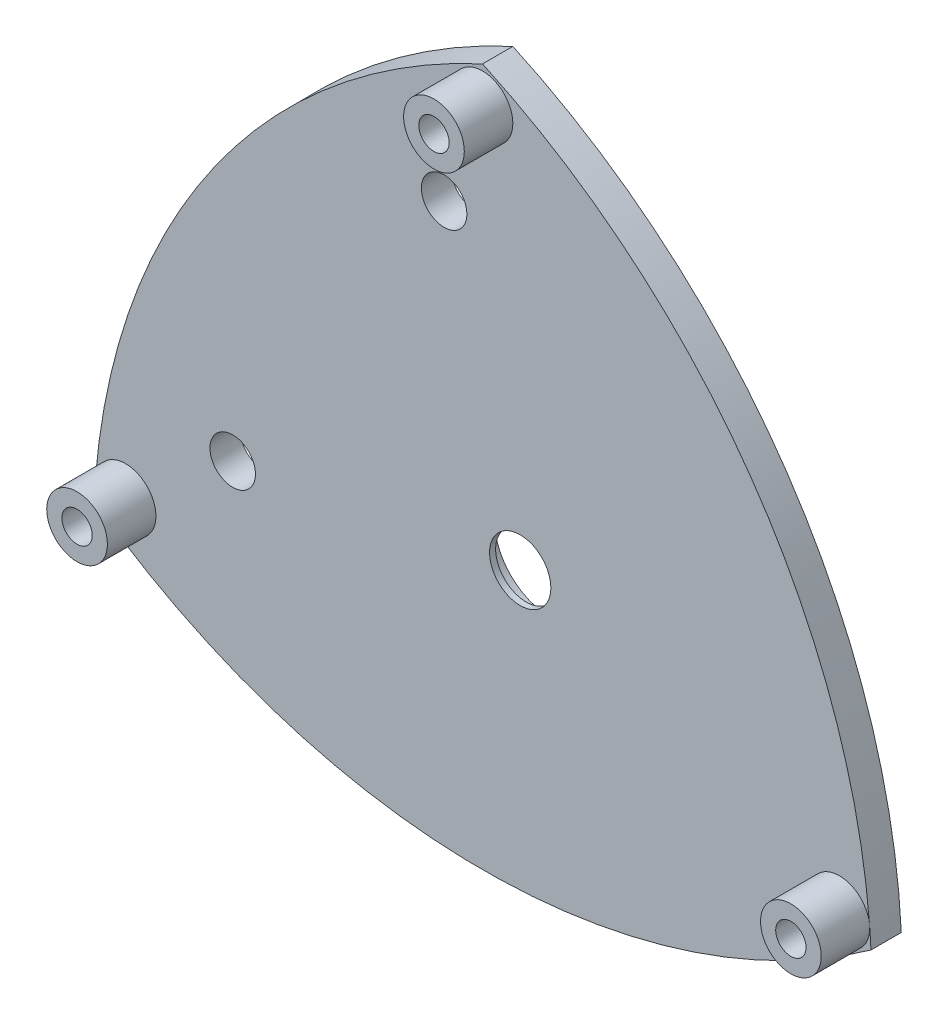
SolidWorks part; units mm, degrees
ref_plane "前视基准面" through (0, 0, 0) normal (0, 0, 1) x (1, 0, 0)
ref_plane "上视基准面" through (0, 0, 0) normal (0, 1, 0) x (1, 0, 0)
ref_plane "右视基准面" through (0, 0, 0) normal (1, 0, 0) x (0, 0, -1)
sketch "草图1" plane through (0, 0, 0) normal (0, 0, 1) x (1, 0, 0)
  line L0 (0, -115) -> (0, 115) construction
  line L2 (0, 0) -> (-128.0227, -73.9139) construction
  line L3 (0, 0) -> (128.0227, -73.9139) construction
  arc A5 (-128.0227, -73.9139) -> (0, 115) centre (91.6989, -84.9783) cw
  arc A6 (-128.0227, -73.9139) -> (128.0227, -73.9139) centre (0, 105) ccw
  arc A7 (128.0227, -73.9139) -> (0, 115) centre (-91.6989, -84.9783) ccw
  circle A8 centre (0, 103) radius 5
  circle A9 centre (-117.6304, -67.9139) radius 5
  circle A10 centre (117.6304, -67.9139) radius 5
  point P8 (-117.6304, -67.9139)
  point P11 (0, 103)
  point P12 (117.6304, -67.9139)
  dimension "D1" = 220
  dimension "D7" = 10
  dimension "D8" = 10
  dimension "D9" = 10
  dimension "D2" = 12
  dimension "D3" = 12
  dimension "D4" = 12
  dimension "D5" = 120
  dimension "D6" = 230
extrude "凸台-拉伸1" add sketch "草图1" along normal blind 10
sketch "草图2" plane through (0, 0, 10) normal (0, 0, 1) x (1, 0, 0)
  circle A0 centre (0, 103) radius 5
  circle A1 centre (0, 103) radius 10
  circle A2 centre (-117.6304, -67.9139) radius 5
  circle A3 centre (-117.6304, -67.9139) radius 10
  circle A4 centre (117.6304, -67.9139) radius 5
  circle A5 centre (117.6304, -67.9139) radius 10
  dimension "D1" = 20
  dimension "D2" = 20
  dimension "D3" = 20
extrude "凸台-拉伸2" add sketch "草图2" along normal blind 16
sketch "草图3" plane through (0, 0, 0) normal (0, 0, -1) x (-1, 0, 0)
  circle A0 centre (12.651, 69.5155) radius 7.5
  circle A1 centre (82.3341, -39.5307) radius 7.5
extrude "切除-拉伸1" cut sketch "草图3" against normal blind 10
sketch "草图4" plane through (0, 0, 10) normal (0, 0, 1) x (1, 0, 0)
  circle A0 centre (12.4253, -23.2965) radius 18.5
  dimension "D1" = 37
extrude "切除-拉伸2" cut sketch "草图4" against normal blind 10
sketch "草图5" plane through (0, 0, 10) normal (0, 0, 1) x (1, 0, 0)
  circle A0 centre (12.4253, -23.2965) radius 18.5
  circle A1 centre (12.4253, -23.2965) radius 10.1
  dimension "D1" = 20.2
extrude "凸台-拉伸3" add sketch "草图5" against normal blind 2
